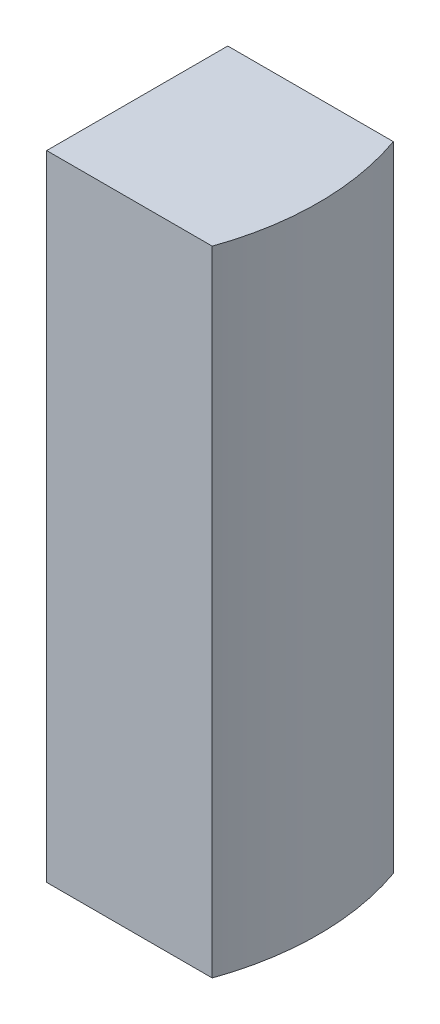
SolidWorks part; units mm, degrees
ref_plane "前视基准面" through (0, 0, 0) normal (0, 0, 1) x (1, 0, 0)
ref_plane "上视基准面" through (0, 0, 0) normal (0, 1, 0) x (1, 0, 0)
ref_plane "右视基准面" through (0, 0, 0) normal (1, 0, 0) x (0, 0, -1)
sketch "草图1" plane through (0, 0, 0) normal (0, 1, 0) x (1, 0, 0)
  line L0 (-56.5685, -20) -> (56.5685, -20)
  line L1 (-56.5685, 20) -> (56.5685, 20)
  line L2 (-20, 56.5685) -> (-20, -56.5685)
  line L3 (20, 56.5685) -> (20, -56.5685)
  circle A0 centre (0, 0) radius 60
  dimension "D1" = 120
  dimension "D2" = 20
  dimension "D3" = 20
  dimension "D4" = 20
  dimension "D5" = 20
extrude "凸台-拉伸1" add sketch "草图1" along normal blind 140 contours L0 A0 L1 L3
